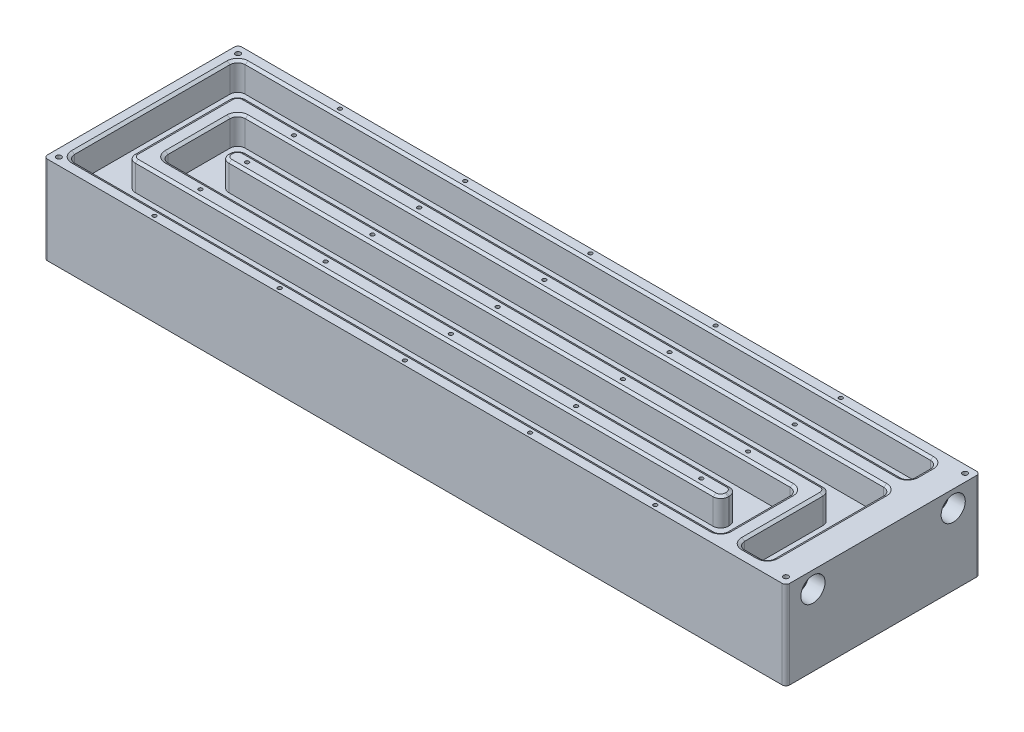
SolidWorks part; units mm, degrees
ref_plane "Front Plane" through (0, 0, 0) normal (0, 0, 1) x (1, 0, 0)
ref_plane "Top Plane" through (0, 0, 0) normal (0, 1, 0) x (1, 0, 0)
ref_plane "Right Plane" through (0, 0, 0) normal (1, 0, 0) x (0, 0, -1)
sketch "Sketch1" plane through (0, 0, 0) normal (0, 1, 0) x (1, 0, 0)
  line L1 (-244.475, 67) -> (244.475, 67)
  line L2 (-244.475, 67) -> (-244.475, -67)
  line L3 (-244.475, -67) -> (244.475, -67)
  line L4 (244.475, 67) -> (244.475, -67)
  line L5 (-244.475, 67) -> (244.475, -67) construction
  line L6 (-244.475, -67) -> (244.475, 67) construction
  point P0 (0, 0)
  dimension "D1" = 134
  dimension "D2" = 488.95
extrude "Boss-Extrude1" add sketch "Sketch1" along normal blind 58
hole_wizard "3/8 NPT Tapped Hole1" positions "Sketch2" profile "Sketch3" size "3/8" standard "ANSI Inch"
sketch "Sketch2" plane through (244.475, 0, 0) normal (1, 0, 0) x (0, 0, -1)
  line L0 (46.2, 47) -> (-46.2, 47) construction
  line L4 (-67, 58) -> (67, 58) construction
  point P0 (-46.2, 47)
  point P2 (46.2, 47)
  point P8 (0, 47)
  dimension "D1" = 92.4
  dimension "D2" = 11
sketch "Sketch3" plane through (244.475, 47, 46.2) normal (0, 1, 0) x (0, 0, -1)
  line L0 (0, 0) -> (0, 21.6686)
  line L1 (7.1374, 17.38) -> (0, 21.6686)
  line L2 (-7.1374, 17.38) -> (0, 21.6686) construction
  line L3 (7.1374, 17.38) -> (7.1374, 10.33)
  line L4 (7.1374, 10.33) -> (7.6537, 10.33)
  line L5 (7.6537, 10.33) -> (7.963, 0)
  line L6 (-7.6537, 10.33) -> (-7.963, 0) construction
  line L7 (7.963, 0) -> (0, 0)
  line L8 (0, -6.35) -> (0, 107.95) construction
  line L11 (-7.1374, 10.33) -> (-7.6537, 10.33) construction
  dimension "Tap Drill Dia." = 14.2748
  dimension "Tap Drill Depth" = 17.38
  dimension "Thread Dia." = 15.9261
  dimension "Thread Angle" = 3.43
  dimension "Thread Depth" = 10.33
  dimension "Drill Angle" = 118
cosmetic thread "Hole Thread1" parameters "D1"=10.33, "D2"=17.145
cosmetic thread "Hole Thread2" parameters "D1"=10.33, "D2"=17.145
sketch "Sketch4" plane through (0, 58, 0) normal (0, 1, 0) x (1, 0, 0)
  line L0 (-244.475, 67) -> (-244.475, -67) construction
  line L1 (224.475, 56.2) -> (-236.975, 56.2)
  line L2 (224.475, 56.2) -> (224.475, 36.2)
  line L3 (224.475, 36.2) -> (-236.975, 36.2)
  line L4 (-236.975, 56.2) -> (-236.975, 36.2)
  line L5 (244.475, 67) -> (-244.475, 67) construction
  line L6 (244.475, -67) -> (244.475, 67) construction
  dimension "D1" = 7.5
  dimension "D2" = 10.8
  dimension "D3" = 20
  dimension "D4" = 20
extrude "Cut-Extrude1" cut sketch "Sketch4" against normal blind 18
pattern_linear "LPattern1" count 4 spacing 30.8 along (0, 0, 1) of "Cut-Extrude1"
sketch "Sketch5" plane through (0, 58, 0) normal (0, 1, 0) x (1, 0, 0)
  line L0 (224.475, 25.4) -> (-236.975, 25.4) construction
  line L1 (-236.975, -25.4) -> (-206.175, -25.4)
  line L2 (-236.975, -25.4) -> (-236.975, 25.4)
  line L3 (-236.975, 25.4) -> (-206.175, 25.4)
  line L4 (-206.175, -25.4) -> (-206.175, 25.4)
  dimension "D1" = 30.8
extrude "Boss-Extrude2" add sketch "Sketch5" against normal up to next
sketch "Sketch6" plane through (0, 58, 0) normal (0, 1, 0) x (1, 0, 0)
  line L0 (224.475, -5.4) -> (-206.175, -5.4) construction
  line L1 (224.475, -56.2) -> (193.675, -56.2)
  line L2 (224.475, -56.2) -> (224.475, -5.4)
  line L3 (224.475, -5.4) -> (193.675, -5.4)
  line L4 (193.675, -56.2) -> (193.675, -5.4)
  dimension "D1" = 30.8
extrude "Boss-Extrude3" add sketch "Sketch6" against normal up to next
sketch "Sketch7" plane through (0, 58, 0) normal (0, 1, 0) x (1, 0, 0)
  line L0 (-206.175, 5.4) -> (224.475, 5.4) construction
  line L1 (204.475, 5.4) -> (224.475, 5.4)
  line L2 (204.475, 5.4) -> (204.475, -56.2)
  line L3 (204.475, -56.2) -> (224.475, -56.2)
  line L4 (224.475, 5.4) -> (224.475, -56.2)
  line L5 (-244.475, -67) -> (244.475, -67) construction
  line L6 (193.675, -36.2) -> (193.675, -56.2) construction
  dimension "D1" = 20
  dimension "D2" = 10.8
  dimension "D3" = 10.8
extrude "Cut-Extrude2" cut sketch "Sketch7" against normal blind 18
sketch "Sketch8" plane through (0, 58, 0) normal (0, 1, 0) x (1, 0, 0)
  line L0 (-206.175, -25.4) -> (193.675, -25.4) construction
  line L1 (193.675, -36.2) -> (173.675, -36.2)
  line L2 (193.675, -36.2) -> (193.675, -25.4)
  line L3 (193.675, -25.4) -> (173.675, -25.4)
  line L4 (173.675, -36.2) -> (173.675, -25.4)
  dimension "D1" = 20
extrude "Cut-Extrude3" cut sketch "Sketch8" against normal blind 18
sketch "Sketch9" plane through (0, 58, 0) normal (0, 1, 0) x (1, 0, 0)
  line L0 (-236.975, 36.2) -> (224.475, 36.2) construction
  line L1 (-236.975, -36.2) -> (-216.975, -36.2)
  line L2 (-236.975, -36.2) -> (-236.975, 36.2)
  line L3 (-236.975, 36.2) -> (-216.975, 36.2)
  line L4 (-216.975, -36.2) -> (-216.975, 36.2)
  dimension "D1" = 20
extrude "Cut-Extrude4" cut sketch "Sketch9" against normal blind 18
sketch "Sketch10" plane through (0, 58, 0) normal (0, 1, 0) x (1, 0, 0)
  line L0 (-206.175, 5.4) -> (204.475, 5.4) construction
  line L1 (-206.175, -5.4) -> (-186.175, -5.4)
  line L2 (-206.175, -5.4) -> (-206.175, 5.4)
  line L3 (-206.175, 5.4) -> (-186.175, 5.4)
  line L4 (-186.175, -5.4) -> (-186.175, 5.4)
  dimension "D1" = 20
extrude "Cut-Extrude5" cut sketch "Sketch10" against normal blind 18
fillet "Fillet1" radius 5 18 edges at (193.675, 49, 5.4) (173.675, 49, 25.4) (173.675, 49, 36.2) (193.675, 49, 56.2) (204.475, 49, 56.2) (224.475, 49, 56.2) (204.475, 49, -5.4) (-206.175, 49, -25.4) (224.475, 49, -25.4) (224.475, 49, -36.2) (224.475, 49, -56.2) (-216.975, 49, -36.2) (-216.975, 49, 36.2) (-236.975, 49, 56.2) (-186.175, 49, -5.4) (-186.175, 49, 5.4) (-206.175, 49, 25.4) (-236.975, 49, -56.2)
chamfer "Chamfer1" distance 2 angle 30 36 edges at (3.75, 58, 5.4) (193.675, 58, 30.8) (173.675, 58, 30.8) (-16.25, 58, 25.4) (-206.175, 58, 0) (9.15, 58, -25.4) (224.475, 58, 15.4) (214.475, 58, 56.2) (204.475, 58, 25.4) (9.15, 58, -5.4) (-186.175, 58, 0) (-21.65, 58, 56.2) (-236.975, 58, 0) (-6.25, 58, -56.2) (224.475, 58, -46.2) (3.75, 58, -36.2) (-216.975, 58, 0) (-21.65, 58, 36.2) (-184.7105, 58, 3.9355) (-184.7105, 58, -3.9355) (-215.5105, 58, 34.7355) (-215.5105, 58, -34.7355) (203.0105, 58, -3.9355) (172.2105, 58, 34.7355) (172.2105, 58, 26.8645) (192.2105, 58, 6.8645) (192.2105, 58, 54.7355) (205.9395, 58, 54.7355) (223.0105, 58, 54.7355) (223.0105, 58, -23.9355) (223.0105, 58, -37.6645) (223.0105, 58, -54.7355) (-235.5105, 58, 54.7355) (-204.7105, 58, 23.9355) (-204.7105, 58, -23.9355) (-235.5105, 58, -54.7355)
hole_wizard "Tap Drill for M3x0.5 - Plate Next Mounts" positions "Sketch13" profile "Sketch14" hole size "M3x0.5" standard "ANSI Metric"
sketch "Sketch13" plane through (0, 0, 0) normal (0, -1, 0) x (-1, 0, 0)
  line L0 (191.975, -30.8) -> (191.975, 30.8) construction
  line L3 (244.475, 67) -> (244.475, -67) construction
  point P0 (191.975, -30.8)
  point P2 (191.975, 30.8)
  point P10 (191.975, 0)
  point P13 (244.475, 0)
  dimension "D1" = 61.6
  dimension "D2" = 52.5
sketch "Sketch14" plane through (-191.975, 0, 30.8) normal (1, 0, 0) x (0, 0, -1)
  line L0 (0, 0) -> (0, 10.7511)
  line L1 (0, 10.7511) -> (1.25, 10)
  line L2 (1.25, 10) -> (1.25, 0)
  line L5 (1.25, 0) -> (0, 0)
  line L10 (0, 10.7511) -> (-1.25, 10) construction
  line L11 (0, -6.35) -> (0, 107.95) construction
  dimension "Hole Dia." = 2.5
  dimension "Hole Depth" = 10
  dimension "Drill Angle" = 118
pattern_linear "LPattern2" count 5 spacing 97.75 along (1, 0, 0) of "Tap Drill for M3x0.5 - Plate Next Mounts"
sketch "Sketch15" plane through (0, 58, 0) normal (0, 1, 0) x (1, 0, 0)
  line L0 (-244.475, 67) -> (-244.475, -67) construction
  line L1 (244.475, -67) -> (-244.475, -67)
  line L2 (244.475, -67) -> (244.475, -64)
  line L3 (244.475, -64) -> (-244.475, -64)
  line L4 (-244.475, -67) -> (-244.475, -64)
  dimension "D1" = 3
extrude "Cut-Extrude6" cut sketch "Sketch15" against normal through all
sketch "Sketch16" plane through (0, 58, 0) normal (0, 1, 0) x (1, 0, 0)
  line L0 (-244.475, 67) -> (-244.475, -64) construction
  line L1 (244.475, 67) -> (-244.475, 67)
  line L2 (244.475, 67) -> (244.475, 64)
  line L3 (244.475, 64) -> (-244.475, 64)
  line L4 (-244.475, 67) -> (-244.475, 64)
  dimension "D1" = 3
extrude "Cut-Extrude7" cut sketch "Sketch16" against normal through all
fillet "Fillet2" radius 2.5 4 edges at (-244.475, 29, 64) (-244.475, 29, -64) (244.475, 29, 64) (244.475, 29, -64)
hole_wizard "Tap Drill for M3x0.5 Tap1" positions "Sketch11" profile "Sketch12" hole size "M3x0.5" standard "ANSI Metric"
sketch "Sketch11" plane through (0, 58, 0) normal (0, 1, 0) x (1, 0, 0)
  line L2 (-244.475, 61.5) -> (-244.475, -61.5) construction
  line L3 (-174.475, 34.2) -> (-174.475, 27.4) construction
  line L4 (219.475, 34.2) -> (-211.975, 34.2) construction
  line L5 (-201.175, 27.4) -> (219.475, 27.4) construction
  line L8 (-174.475, -27.4) -> (-174.475, -34.2) construction
  line L9 (168.675, -27.4) -> (-201.175, -27.4) construction
  line L10 (-211.975, -34.2) -> (168.675, -34.2) construction
  line L21 (-174.475, -58.2) -> (-174.475, -64) construction
  line L22 (188.675, -58.2) -> (-231.975, -58.2) construction
  line L23 (241.975, -64) -> (-241.975, -64) construction
  line L26 (-174.475, -3.4) -> (-174.475, 3.4) construction
  line L27 (-181.175, -3.4) -> (188.675, -3.4) construction
  line L28 (199.475, 3.4) -> (-181.175, 3.4) construction
  line L31 (-174.475, 58.2) -> (-174.475, 64) construction
  line L32 (-231.975, 58.2) -> (219.475, 58.2) construction
  line L33 (-241.975, 64) -> (241.975, 64) construction
  point P0 (-174.475, 0)
  point P11 (-174.475, -30.8)
  point P13 (-174.475, -61.1)
  point P15 (-174.475, 30.8)
  point P17 (-174.475, 61.1)
  point P48 (-174.475, -30.8)
  point P49 (-174.475, 30.8)
  point P72 (-174.475, -61.1)
  point P91 (-174.475, 61.1)
  dimension "D2" = 70
sketch "Sketch12" plane through (-174.475, 58, 0) normal (1, 0, 0) x (0, 0, 1)
  line L0 (0, 0) -> (0, 10.7511)
  line L1 (0, 10.7511) -> (1.25, 10)
  line L2 (1.25, 10) -> (1.25, 0)
  line L5 (1.25, 0) -> (0, 0)
  line L10 (0, 10.7511) -> (-1.25, 10) construction
  line L11 (0, -6.35) -> (0, 107.95) construction
  dimension "Hole Dia." = 2.5
  dimension "Hole Depth" = 10
  dimension "Drill Angle" = 118
sketch "Sketch17" [suppressed] plane through (0, 0, 0) normal (0, -1, 0) x (-1, 0, 0)
  line L0 (-199.075, -30.7906) -> (-199.025, -30.8) construction
  line L1 (-202.475, -27.6993) -> (-195.675, -27.6993) construction
  line L2 (-202.475, -51.2) -> (-202.475, 0.4) construction
  line L3 (-195.675, -10.4) -> (-195.675, -51.2) construction
  point P0 (-199.075, -30.7906)
  point P10 (-199.075, -27.6993)
pattern_linear "LPattern3" count 5 spacing 82.5 along (1, 0, 0) of "Tap Drill for M3x0.5 Tap1"
hole_wizard "Tap Drill for M3x0.5 Tap3" [suppressed] positions "Sketch18" profile "Sketch19" hole size "M3x0.5" standard "ANSI Metric"
sketch "Sketch18" plane through (0, 22, 0) normal (0, 1, 0) x (1, 0, 0)
  line L0 (188.675, -58.2) -> (188.675, -64) construction
  line L1 (241.975, -64) -> (-241.975, -64) construction
  line L4 (202.475, -51.2) -> (195.675, -51.2) construction
  line L7 (202.475, -30.8) -> (195.675, -30.8) construction
  line L8 (202.475, -51.2) -> (202.475, 0.4) construction
  line L9 (195.675, -10.4) -> (195.675, -51.2) construction
  line L12 (195.675, -10.4) -> (202.475, -10.4) construction
  line L15 (188.675, -3.4) -> (188.675, 3.4) construction
  line L16 (199.475, 3.4) -> (-181.175, 3.4) construction
  point P0 (199.075, -30.8)
  point P2 (188.675, 0)
  point P4 (199.075, -10.4)
  point P6 (199.075, -51.2)
  point P8 (188.675, -61.1)
  point P51 (199.075, -10.4)
  point P52 (199.075, -30.8)
  point P53 (199.075, -51.2)
  point P54 (188.675, -61.1)
sketch "Sketch19" plane through (199.075, 22, 30.8) normal (1, 0, 0) x (0, 0, 1)
  line L0 (0, 0) -> (0, 10.7511)
  line L1 (0, 10.7511) -> (1.25, 10)
  line L2 (1.25, 10) -> (1.25, 0)
  line L5 (1.25, 0) -> (0, 0)
  line L10 (0, 10.7511) -> (-1.25, 10) construction
  line L11 (0, -6.35) -> (0, 107.95) construction
  dimension "Hole Dia." = 2.5
  dimension "Hole Depth" = 10
  dimension "Drill Angle" = 118
hole_wizard "Tap Drill for M3x0.5 Tap4" [suppressed] positions "Sketch20" profile "Sketch21" hole size "M3x0.5" standard "ANSI Metric"
sketch "Sketch20" [suppressed] plane through (0, 22, 0) normal (0, 1, 0) x (1, 0, 0)
  line L0 (229.975, -56) -> (229.975, 56) construction
  line L2 (226.475, 20.4) -> (226.475, -51.2) construction
  line L3 (219.475, 27.4) -> (219.475, 34.2) construction
  line L4 (-201.175, 27.4) -> (219.475, 27.4) construction
  line L5 (219.475, 34.2) -> (-211.975, 34.2) construction
  line L8 (219.475, 58.2) -> (219.475, 64) construction
  line L9 (-231.975, 58.2) -> (219.475, 58.2) construction
  line L10 (-241.975, 64) -> (241.975, 64) construction
  line L13 (214.475, -58.2) -> (214.475, -64) construction
  line L14 (219.475, -58.2) -> (209.475, -58.2) construction
  line L15 (241.975, -64) -> (-241.975, -64) construction
  line L18 (199.075, -10.4) -> (229.975, -10.4) construction
  line L20 (229.975, -56) -> (229.975, -36) construction
  point P0 (219.475, 61.1)
  point P2 (219.475, 30.8)
  point P4 (229.975, 36)
  point P6 (229.975, 56)
  point P8 (229.975, 20.4)
  point P10 (229.975, -10.4)
  point P12 (229.975, -36)
  point P14 (229.975, -56)
  point P16 (214.475, -61.1)
  point P52 (214.475, -61.1)
  point P53 (214.475, -58.2)
  point P54 (219.475, 30.8)
  point P55 (219.475, 61.1)
  dimension "D1" = 3.5
  dimension "D2" = 20
  dimension "D3" = 20
  dimension "D4" = 8
  dimension "D5" = 8
sketch "Sketch21" plane through (219.475, 22, -61.1) normal (1, 0, 0) x (0, 0, 1)
  line L0 (0, 0) -> (0, 10.7511)
  line L1 (0, 10.7511) -> (1.25, 10)
  line L2 (1.25, 10) -> (1.25, 0)
  line L5 (1.25, 0) -> (0, 0)
  line L10 (0, 10.7511) -> (-1.25, 10) construction
  line L11 (0, -6.35) -> (0, 107.95) construction
  dimension "Hole Dia." = 2.5
  dimension "Hole Depth" = 10
  dimension "Drill Angle" = 118
hole_wizard "Tap Drill for M4x0.7 Tap1" positions "Sketch22" profile "Sketch23" hole size "M4x0.7" standard "ANSI Metric"
sketch "Sketch22" plane through (0, 58, 0) normal (0, 1, 0) x (1, 0, 0)
  line L0 (-239.475, -59) -> (-239.475, 59) construction
  line L1 (-239.475, 59) -> (239.475, 59) construction
  line L2 (239.475, 59) -> (239.475, -59) construction
  line L3 (239.475, -59) -> (-239.475, -59) construction
  line L6 (241.975, -64) -> (-241.975, -64) construction
  line L7 (-244.475, 61.5) -> (-244.475, -61.5) construction
  line L8 (-241.975, 64) -> (241.975, 64) construction
  line L9 (244.475, -61.5) -> (244.475, 61.5) construction
  point P0 (239.475, -59)
  point P2 (239.475, 59)
  point P4 (-239.475, 59)
  point P6 (-239.475, -59)
  dimension "D1" = 5
  dimension "D2" = 5
  dimension "D3" = 5
  dimension "D4" = 5
sketch "Sketch23" plane through (239.475, 58, 59) normal (1, 0, 0) x (0, 0, 1)
  line L0 (0, 0) -> (0, 18.3714)
  line L1 (0, 18.3714) -> (1.65, 17.38)
  line L2 (1.65, 17.38) -> (1.65, 0)
  line L5 (1.65, 0) -> (0, 0)
  line L10 (0, 18.3714) -> (-1.65, 17.38) construction
  line L11 (0, -6.35) -> (0, 107.95) construction
  dimension "Hole Dia." = 3.3
  dimension "Hole Depth" = 17.38
  dimension "Drill Angle" = 118
hole_wizard "Tap Drill for M3x0.5 Tap5" [suppressed] positions "Sketch24" profile "Sketch25" hole size "M3x0.5" standard "ANSI Metric"
sketch "Sketch24" plane through (0, 22, 0) normal (0, 1, 0) x (1, 0, 0)
  line L0 (-208.175, -20.4) -> (-214.975, -20.4) construction
  line L1 (-214.975, 31.2) -> (-214.975, -31.2) construction
  line L4 (-208.175, 0) -> (-214.975, 0) construction
  line L5 (-208.175, -20.4) -> (-208.175, 20.4) construction
  line L8 (-208.175, 20.4) -> (-214.975, 20.4) construction
  line L11 (-201.175, 27.4) -> (-201.175, 34.2) construction
  line L12 (219.475, 34.2) -> (-211.975, 34.2) construction
  line L15 (-201.175, -27.4) -> (-201.175, -34.2) construction
  line L16 (-211.975, -34.2) -> (168.675, -34.2) construction
  line L19 (-238.975, -51.2) -> (-244.475, -51.2) construction
  line L20 (-244.475, 61.5) -> (-244.475, -61.5) construction
  line L23 (-238.975, 0) -> (-244.475, 0) construction
  line L24 (-238.975, -51.2) -> (-238.975, 51.2) construction
  line L27 (-238.975, 51.2) -> (-244.475, 51.2) construction
  line L30 (-224.475, 58.2) -> (-224.475, 64) construction
  line L31 (-231.975, 58.2) -> (219.475, 58.2) construction
  line L32 (-241.975, 64) -> (241.975, 64) construction
  line L35 (-224.475, -58.2) -> (-224.475, -64) construction
  line L36 (188.675, -58.2) -> (-231.975, -58.2) construction
  line L37 (241.975, -64) -> (-241.975, -64) construction
  arc A0 (-201.175, 27.4) -> (-208.175, 20.4) centre (-201.175, 20.4) ccw construction
  point P0 (-211.575, 0)
  point P2 (-211.575, -20.4)
  point P4 (-211.575, 20.4)
  point P6 (-201.175, 30.8)
  point P8 (-201.175, -30.8)
  point P10 (-224.475, -61.1)
  point P12 (-241.725, -51.2)
  point P14 (-241.725, 0)
  point P16 (-241.725, 51.2)
  point P18 (-224.475, 61.1)
  point P100 (-241.725, -51.2)
  point P101 (-224.475, -61.1)
  point P102 (-201.175, -30.8)
  point P103 (-211.575, -20.4)
  point P104 (-211.575, 0)
  point P105 (-241.725, 0)
  point P106 (-211.575, 20.4)
  point P107 (-201.175, 30.8)
  point P108 (-224.475, 61.1)
  point P109 (-241.725, 51.2)
  dimension "D1" = 20
  dimension "D2" = 20
sketch "Sketch25" plane through (-211.575, 22, 0) normal (1, 0, 0) x (0, 0, 1)
  line L0 (0, 0) -> (0, 10.7511)
  line L1 (0, 10.7511) -> (1.25, 10)
  line L2 (1.25, 10) -> (1.25, 0)
  line L5 (1.25, 0) -> (0, 0)
  line L10 (0, 10.7511) -> (-1.25, 10) construction
  line L11 (0, -6.35) -> (0, 107.95) construction
  dimension "Hole Dia." = 2.5
  dimension "Hole Depth" = 10
  dimension "Drill Angle" = 118
